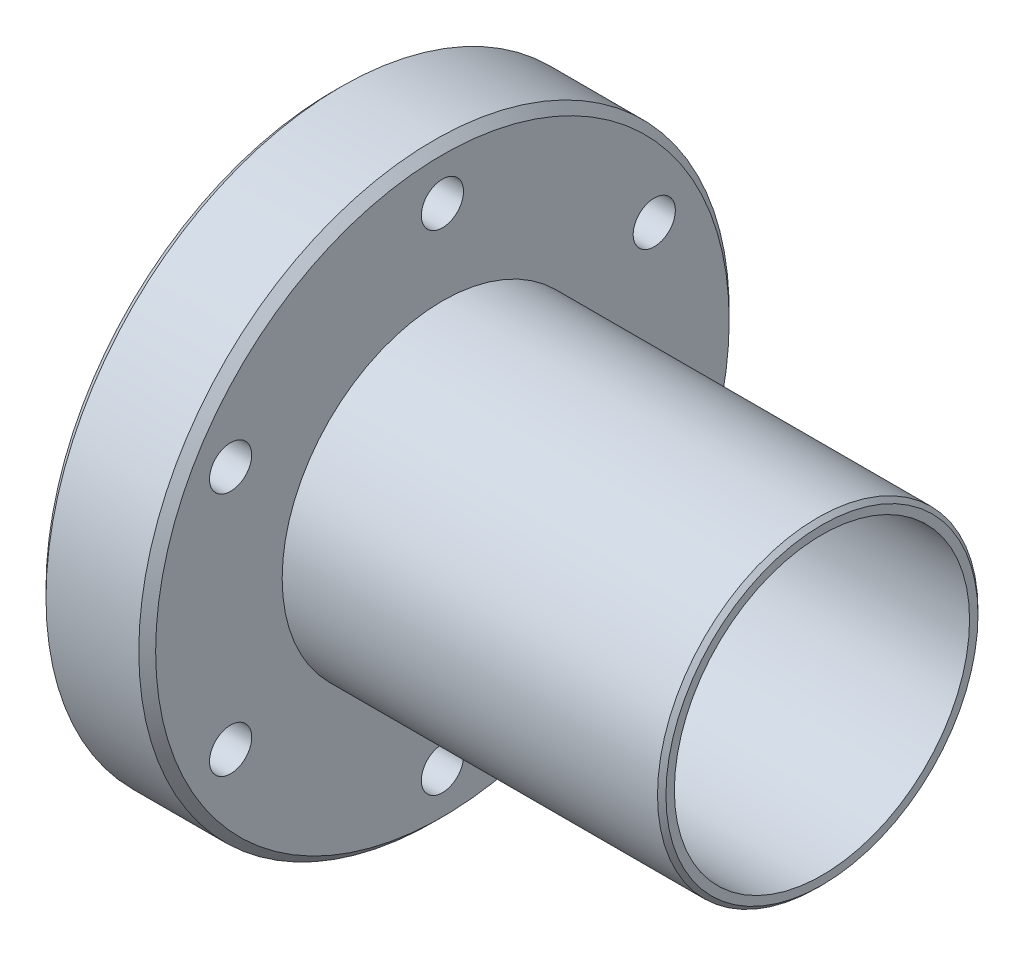
SolidWorks part; units mm, degrees
ref_plane "정면" through (0, 0, 0) normal (0, 0, 1) x (1, 0, 0)
ref_plane "윗면" through (0, 0, 0) normal (0, 1, 0) x (1, 0, 0)
ref_plane "우측면" through (0, 0, 0) normal (1, 0, 0) x (0, 0, -1)
sketch "스케치1" plane through (0, 0, 0) normal (0, 0, 1) x (1, 0, 0)
  line L0 (0, 17.5) -> (0, 35)
  line L1 (0, 35) -> (13, 35)
  line L2 (13, 35) -> (13, 19)
  line L3 (13, 19) -> (58, 19)
  line L4 (58, 19) -> (58, 17.5)
  line L5 (58, 17.5) -> (0, 17.5)
  line L6 (0, 0) -> (59.8351, 0) construction
  dimension "D1" = 35
  dimension "D2" = 38
  dimension "D3" = 13
  dimension "D4" = 70
  dimension "D5" = 58
revolve "회전1" add sketch "스케치1" angle 360 about L6
sketch "스케치2" plane through (0, 0, 0) normal (-1, 0, 0) x (0, 0, 1)
  circle A0 centre (0, 0) radius 29 construction
  point P3 (0, 29)
  dimension "D1" = 58
hole_wizard "M6 나사 구멍1" positions "스케치2" profile "스케치3" tap size "M6" standard "ISO" end condition through all
sketch "스케치3" plane through (0, 29, 0) normal (0, 1, 0) x (0, 0, 1)
  line L0 (0, 0) -> (0, 58)
  line L1 (0, 58) -> (2.5, 58)
  line L2 (2.5, 58) -> (2.5, 0)
  line L5 (2.5, 0) -> (0, 0)
  line L11 (0, -6.35) -> (0, 107.95) construction
  dimension "관통 탭 드릴 지름" = 5
  dimension "관통 탭 드릴 깊이" = 58
cosmetic thread "구멍 나사산1" parameters "D2"=6
pattern_circular "원형 패턴1" count 6 over 360 about axis through (0, 0, 0) along (1, 0, 0) of "M6 나사 구멍1"
cosmetic thread "구멍 나사산2" parameters "D2"=6
cosmetic thread "구멍 나사산3" parameters "D2"=6
cosmetic thread "구멍 나사산4" parameters "D2"=6
cosmetic thread "구멍 나사산5" parameters "D2"=6
cosmetic thread "구멍 나사산6" parameters "D2"=6
chamfer "모따기1" distance 1 angle 45 1 edges at (0, 0, 35)
chamfer "모따기2" distance 1 angle 45 1 edges at (13, 0, 35)
chamfer "모따기3" distance 0.5 angle 45 1 edges at (58, 0, 19)
